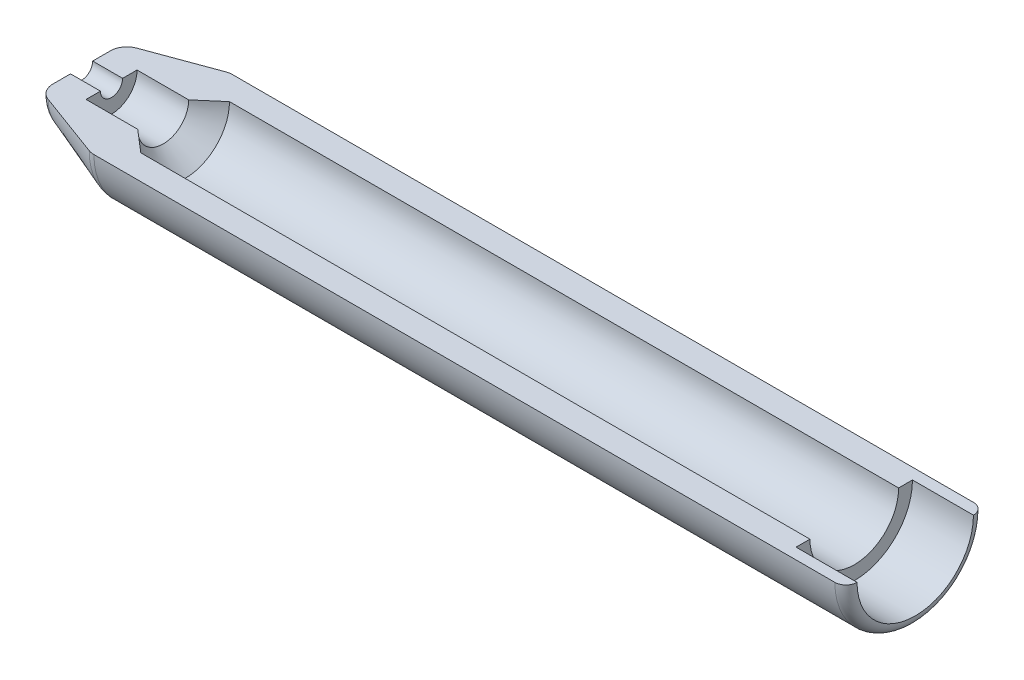
SolidWorks part; units mm, degrees
ref_plane "Front Plane" through (0, 0, 0) normal (0, 0, 1) x (1, 0, 0)
ref_plane "Top Plane" through (0, 0, 0) normal (0, 1, 0) x (1, 0, 0)
ref_plane "Right Plane" through (0, 0, 0) normal (1, 0, 0) x (0, 0, -1)
sketch "Sketch1" plane through (0, 0, 0) normal (0, 1, 0) x (1, 0, 0)
  line L0 (-3.185, 0.1) -> (19.4194, 0.1) construction
  line L1 (-2.4261, 0.9) -> (-1.2536, 1.3315)
  line L2 (12.4176, 1.15) -> (11.3176, 1.15)
  line L3 (11.3176, 1.15) -> (11.3176, 0.9)
  line L4 (2.9176, 0.9) -> (3.6176, 0.9)
  line L7 (-2.0824, 0.3) -> (-2.0824, 0.56)
  line L9 (3.6176, 0.9) -> (11.3176, 0.9)
  line L14 (-2.0824, 0.3) -> (-2.6225, 0.3)
  line L16 (-2.0824, 0.56) -> (-1.15, 0.56)
  line L23 (-1.15, 0.56) -> (-0.7544, 0.9)
  line L24 (12.4176, 5.6171) -> (12.4176, -3.3829) construction
  line L25 (-0.7544, 0.9) -> (2.9176, 0.9)
  line L27 (12.2176, 1.35) -> (-1.15, 1.35)
  line L28 (-2.6225, 0.6185) -> (-2.6225, 0.3)
  arc A0 (-2.4261, 0.9) -> (-2.6225, 0.6185) centre (-2.3225, 0.6185) ccw
  arc A1 (-1.2536, 1.3315) -> (-1.15, 1.35) centre (-1.15, 1.05) cw
  arc A2 (12.2176, 1.35) -> (12.4176, 1.15) centre (12.2176, 1.15) cw
  point P0 (0, 0)
  point P16 (12.4176, 1.35)
  point P24 (12.4176, 1.35)
  dimension "D2" = 0.3
  dimension "D5" = 0.3
  dimension "D6" = 0.46
  dimension "D9" = 0.2
  dimension "D1" = 0.2
  dimension "D3" = 1.25
  dimension "D4" = 0.8
  dimension "D7" = 1.05
  dimension "D8" = 14.5
  dimension "D10" = 1.1
revolve "Revolve1" add sketch "Sketch1" angle 180 about L0
